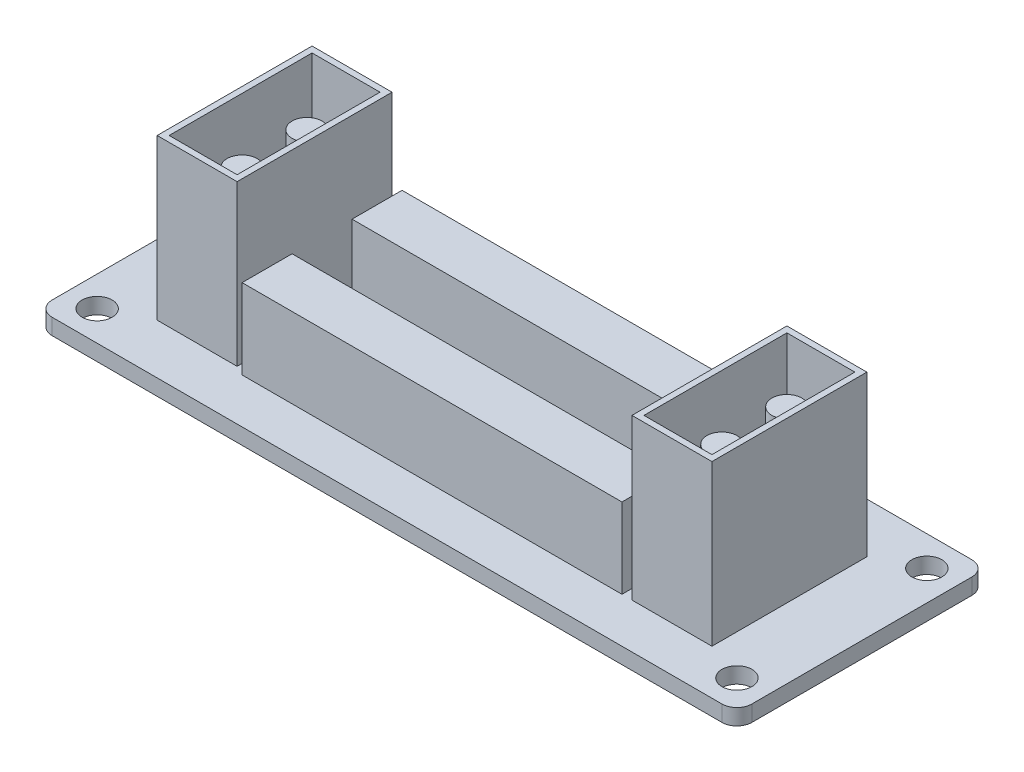
SolidWorks part; units mm, degrees
ref_plane "前视基准面" through (0, 0, 0) normal (0, 0, 1) x (1, 0, 0)
ref_plane "上视基准面" through (0, 0, 0) normal (0, 1, 0) x (1, 0, 0)
ref_plane "右视基准面" through (0, 0, 0) normal (1, 0, 0) x (0, 0, -1)
other "Configuration Table"
sketch "草图2" plane through (0, 0, 0) normal (0, 1, 0) x (1, 0, 0)
  line L1 (-82.3631, 39.0327) -> (-15.3631, 39.0327)
  line L2 (-83.8631, 37.5327) -> (-83.8631, 15.5327)
  line L3 (-82.3631, 14.0327) -> (-15.3631, 14.0327)
  line L4 (-13.8631, 37.5327) -> (-13.8631, 15.5327)
  arc A0 (-83.8631, 15.5327) -> (-82.3631, 14.0327) centre (-82.3631, 15.5327) ccw
  arc A1 (-15.3631, 14.0327) -> (-13.8631, 15.5327) centre (-15.3631, 15.5327) ccw
  arc A2 (-15.3631, 39.0327) -> (-13.8631, 37.5327) centre (-15.3631, 37.5327) cw
  arc A3 (-82.3631, 39.0327) -> (-83.8631, 37.5327) centre (-82.3631, 37.5327) ccw
  point P6 (-83.8631, 14.0327)
  point P11 (-13.8631, 39.0327)
  point P14 (-83.8631, 39.0327)
  dimension "D3" = 1.5
  dimension "D1" = 70
  dimension "D2" = 25
extrude "凸台-拉伸1" add sketch "草图2" along normal blind 1.6
sketch "草图3" plane through (0, 1.6, 0) normal (0, 1, 0) x (1, 0, 0)
  line L0 (-15.3631, 39.0327) -> (-82.3631, 39.0327) construction
  line L1 (-83.8631, 37.5327) -> (-83.8631, 15.5327) construction
  line L2 (-13.8631, 15.5327) -> (-13.8631, 37.5327) construction
  line L3 (-83.8631, 26.5327) -> (-1.9512, 26.5327) construction
  circle A0 centre (-80.8631, 36.0327) radius 1.5
  circle A1 centre (-16.8631, 36.0327) radius 1.5
  circle A2 centre (-16.8631, 17.0327) radius 1.5
  circle A3 centre (-80.8631, 17.0327) radius 1.5
  dimension "D1" = 3
  dimension "D2" = 3
  dimension "D3" = 3
extrude "切除-拉伸1" cut sketch "草图3" against normal blind 1.6
sketch "草图8" plane through (0, 1.6, 0) normal (0, 1, 0) x (1, 0, 0)
  line L0 (-83.8631, 37.5327) -> (-83.8631, 15.5327) construction
  line L1 (-76.8631, 34.5327) -> (-68.8631, 34.5327)
  line L2 (-76.8631, 34.5327) -> (-76.8631, 19.0327)
  line L3 (-76.8631, 19.0327) -> (-68.8631, 19.0327)
  line L4 (-68.8631, 34.5327) -> (-68.8631, 19.0327)
  line L5 (-15.3631, 39.0327) -> (-82.3631, 39.0327) construction
  line L6 (-82.3631, 14.0327) -> (-15.3631, 14.0327) construction
  line L7 (-28.8631, 34.0327) -> (-20.8631, 34.0327)
  line L8 (-28.8631, 34.0327) -> (-28.8631, 18.5327)
  line L9 (-28.8631, 18.5327) -> (-20.8631, 18.5327)
  line L10 (-20.8631, 34.0327) -> (-20.8631, 18.5327)
  line L11 (-13.8631, 15.5327) -> (-13.8631, 37.5327) construction
  dimension "D1" = 7
  dimension "D2" = 8
  dimension "D3" = 15.5
  dimension "D4" = 4.5
  dimension "D5" = 4.5
  dimension "D6" = 8
  dimension "D7" = 7
  dimension "D8" = 15.5
sketch "草图9" plane through (0, 1.6, 0) normal (0, 1, 0) x (1, 0, 0)
extrude "凸台-拉伸2" add sketch "草图8" along normal blind 16
shell "抽壳1" thickness 0.6
sketch "草图11" plane through (0, 0.6, 0) normal (0, 1, 0) x (1, 0, 0)
  line L0 (-68.8631, 34.5327) -> (-76.8631, 34.5327) construction
  line L1 (-76.8631, 19.0327) -> (-68.8631, 19.0327) construction
  line L2 (-24.8631, 34.0327) -> (-24.8631, 18.5327) construction
  line L3 (-20.8631, 34.0327) -> (-28.8631, 34.0327) construction
  line L4 (-28.8631, 18.5327) -> (-20.8631, 18.5327) construction
  circle A0 centre (-72.8631, 30.0327) radius 1.5
  circle A1 centre (-72.8631, 23.5327) radius 1.5
  circle A2 centre (-24.8631, 30.0327) radius 1.5
  circle A4 centre (-24.8631, 23.5327) radius 1.5
  dimension "D1" = 4.5
  dimension "D2" = 4.5
extrude "凸台-拉伸3" add sketch "草图11" along normal blind 14
sketch "草图12" plane through (0, 1.6, 0) normal (0, 1, 0) x (1, 0, 0)
  line L0 (-68.8631, 19.0327) -> (-68.8631, 34.5327) construction
  line L1 (-67.8631, 34.5327) -> (-29.8631, 34.5327)
  line L2 (-67.8631, 34.5327) -> (-67.8631, 29.5327)
  line L3 (-67.8631, 29.5327) -> (-29.8631, 29.5327)
  line L4 (-29.8631, 34.5327) -> (-29.8631, 29.5327)
  line L5 (-28.8631, 34.0327) -> (-28.8631, 18.5327) construction
  line L7 (-15.3631, 39.0327) -> (-82.3631, 39.0327) construction
  line L9 (-29.8631, 18.5327) -> (-67.8631, 18.5327)
  line L10 (-29.8631, 18.5327) -> (-29.8631, 23.5327)
  line L11 (-29.8631, 23.5327) -> (-67.8631, 23.5327)
  line L12 (-67.8631, 18.5327) -> (-67.8631, 23.5327)
  dimension "D1" = 1
  dimension "D2" = 1
  dimension "D3" = 5
  dimension "D4" = 4.5
  dimension "D5" = 5
extrude "凸台-拉伸4" add sketch "草图12" along normal blind 8
sketch "草图16" plane through (0, 1.6, 0) normal (0, 1, 0) x (1, 0, 0)
  line L0 (-67.8631, 18.5327) -> (-67.8631, 14.0327)
  line L1 (-82.3631, 14.0327) -> (-15.3631, 14.0327) construction
  line L2 (-29.8631, 18.5327) -> (-29.8631, 14.0327)
  line L3 (-29.8631, 34.5327) -> (-29.8631, 39.0327)
  line L4 (-15.3631, 39.0327) -> (-82.3631, 39.0327) construction
  line L5 (-67.8631, 34.5327) -> (-67.8631, 39.0327)
sketch "草图17" plane through (0, 0, 0) normal (0, -1, 0) x (1, 0, 0)
  line L10 (-67.8631, -18.5327) -> (-67.8631, -14.0327) construction
  line L11 (-67.8631, -18.5327) -> (-29.8242, -18.5327)
  line L12 (-67.8631, -18.5327) -> (-67.8631, -23.5327)
  line L13 (-67.8631, -23.5327) -> (-29.8242, -23.5327)
  line L14 (-29.8242, -18.5327) -> (-29.8242, -23.5327)
  line L15 (-82.3631, -14.0327) -> (-15.3631, -14.0327) construction
  line L16 (-29.8631, -34.5327) -> (-29.8631, -39.0327) construction
  line L17 (-67.8631, -29.5327) -> (-29.8631, -29.5327)
  line L18 (-67.8631, -29.5327) -> (-67.8631, -34.5327)
  line L19 (-67.8631, -34.5327) -> (-29.8631, -34.5327)
  line L20 (-29.8631, -29.5327) -> (-29.8631, -34.5327)
  line L22 (-15.3631, -39.0327) -> (-82.3631, -39.0327) construction
  dimension "D1" = 4.5
  dimension "D2" = 5
  dimension "D3" = 5
  dimension "D4" = 4.5
extrude "凸台-拉伸5" add sketch "草图17" along normal blind 1
